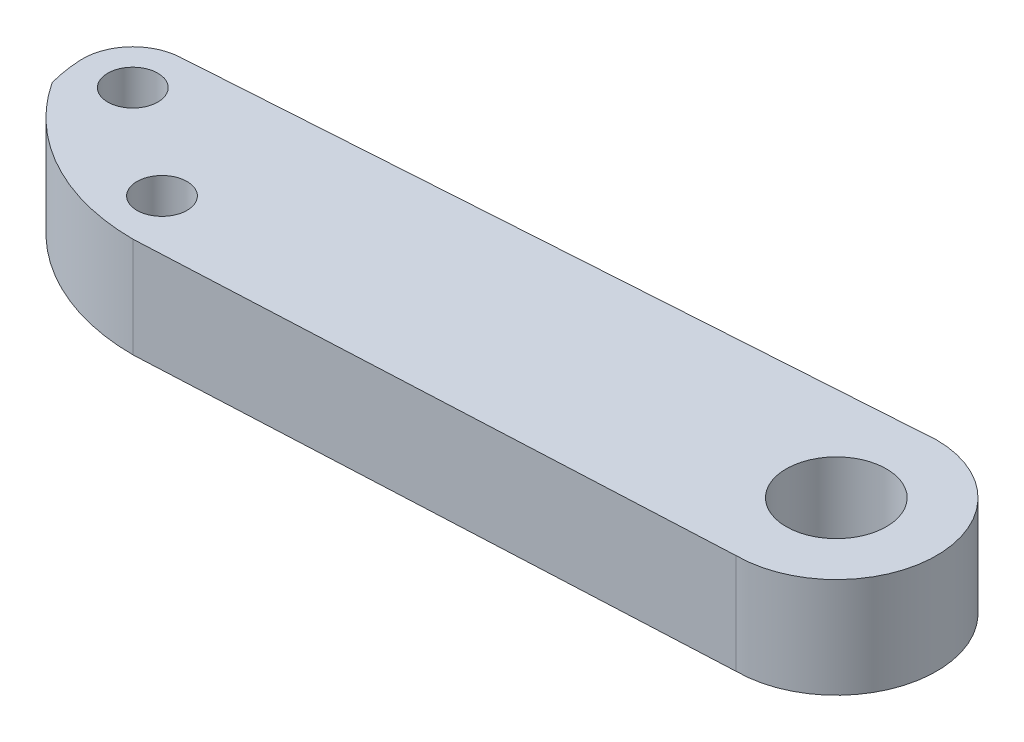
SolidWorks part; units mm, degrees
ref_plane "Front Plane" through (0, 0, 0) normal (0, 0, 1) x (1, 0, 0)
ref_plane "Top Plane" through (0, 0, 0) normal (0, 1, 0) x (1, 0, 0)
ref_plane "Right Plane" through (0, 0, 0) normal (1, 0, 0) x (0, 0, -1)
sketch "Sketch2" plane through (0, 0, 0) normal (0, 1, 0) x (1, 0, 0)
  line L0 (-4.4809, -5.3952) -> (18.484, -4.2974)
  line L2 (-9.8633, 1.8341) -> (18.484, 3.7026)
  line L8 (-11.1515, -2.5962) -> (-12.1138, -0.5181)
  arc A0 (-12.1138, -0.5181) -> (-3.6785, -5.3568) centre (-4.4809, 3.0163) ccw
  circle A1 centre (-5.4057, -3.3213) radius 1
  arc A2 (-11.729, -0.2659) -> (-11.1515, -2.5962) centre (-5.4057, 0.0645) ccw
  arc A4 (-11.729, -0.2659) -> (-9.8633, 1.8341) centre (-9.7318, -0.1615) cw
  circle A5 centre (-9.7318, -0.1615) radius 1
  circle A7 centre (18.484, -0.2974) radius 2
  arc A8 (18.484, -4.2974) -> (17.959, 3.668) centre (18.484, -0.2974) ccw
  point P6 (-11.516, 1.7252)
  dimension "D1" = 30
  dimension "D2" = 2
extrude "Boss-Extrude1" add sketch "Sketch2" along normal blind 4
